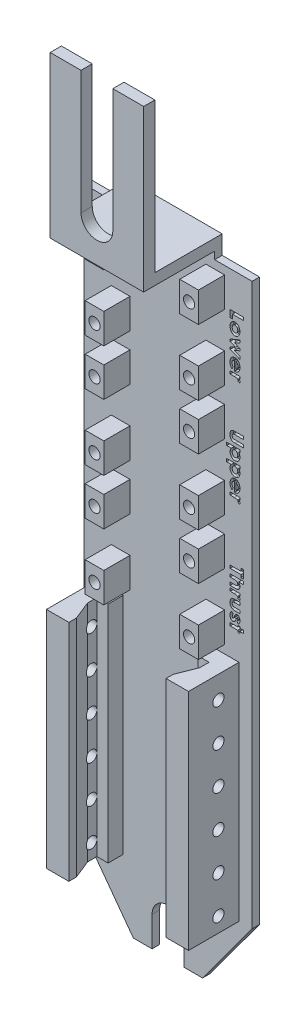
SolidWorks part; units mm, degrees
ref_plane "Front Plane" through (0, 0, 0) normal (0, 0, 1) x (1, 0, 0)
ref_plane "Top Plane" through (0, 0, 0) normal (0, 1, 0) x (1, 0, 0)
ref_plane "Right Plane" through (0, 0, 0) normal (1, 0, 0) x (0, 0, -1)
sketch "Sketch1" plane through (0, 0, 0) normal (0, 0, 1) x (1, 0, 0)
  line L1 (-12.65, -8.8) -> (12.65, -8.8) construction
  line L2 (-12.65, -8.8) -> (-12.65, 8.8) construction
  line L3 (-12.65, 8.8) -> (12.65, 8.8) construction
  line L4 (12.65, -8.8) -> (12.65, 8.8) construction
  line L5 (-12.65, -8.8) -> (12.65, 8.8) construction
  line L6 (-12.65, 8.8) -> (12.65, -8.8) construction
  line L7 (-15.15, 4.8) -> (-10.15, 4.8)
  line L8 (-15.15, 4.8) -> (-15.15, 12.8)
  line L9 (-15.15, 12.8) -> (-10.15, 12.8)
  line L10 (-10.15, 4.8) -> (-10.15, 12.8)
  line L11 (-15.15, 4.8) -> (-10.15, 12.8) construction
  line L12 (-15.15, 12.8) -> (-10.15, 4.8) construction
  line L13 (10.15, 4.8) -> (15.15, 4.8)
  line L14 (10.15, 4.8) -> (10.15, 12.8)
  line L15 (10.15, 12.8) -> (15.15, 12.8)
  line L16 (15.15, 4.8) -> (15.15, 12.8)
  line L17 (10.15, 4.8) -> (15.15, 12.8) construction
  line L18 (10.15, 12.8) -> (15.15, 4.8) construction
  line L19 (10.15, -4.8) -> (15.15, -4.8)
  line L20 (10.15, -4.8) -> (10.15, -12.8)
  line L21 (10.15, -12.8) -> (15.15, -12.8)
  line L22 (15.15, -4.8) -> (15.15, -12.8)
  line L23 (10.15, -4.8) -> (15.15, -12.8) construction
  line L24 (10.15, -12.8) -> (15.15, -4.8) construction
  line L25 (-15.15, -4.8) -> (-10.15, -4.8)
  line L26 (-15.15, -4.8) -> (-15.15, -12.8)
  line L27 (-15.15, -12.8) -> (-10.15, -12.8)
  line L28 (-10.15, -4.8) -> (-10.15, -12.8)
  line L29 (-15.15, -4.8) -> (-10.15, -12.8) construction
  line L30 (-15.15, -12.8) -> (-10.15, -4.8) construction
  circle A0 centre (-12.65, 8.8) radius 1.5
  circle A1 centre (12.65, 8.8) radius 1.5
  circle A2 centre (12.65, -8.8) radius 1.5
  circle A3 centre (-12.65, -8.8) radius 1.5
  point P0 (0, 0)
  dimension "D3" = 3
  dimension "D4" = 3
  dimension "D5" = 3
  dimension "D6" = 3
  dimension "D1" = 25.3
  dimension "D2" = 17.6
  dimension "D7" = 5
  dimension "D8" = 5
  dimension "D9" = 5
  dimension "D10" = 5
  dimension "D11" = 8
  dimension "D12" = 8
  dimension "D13" = 8
  dimension "D14" = 8
extrude "Boss-Extrude1" add sketch "Sketch1" along normal blind 7
sketch "Sketch2" plane through (0, 0, 0) normal (0, 0, -1) x (-1, 0, 0)
  line L1 (-22.5, -15) -> (22.5, -15)
  line L2 (-22.5, -15) -> (-22.5, 15)
  line L3 (-22.5, 15) -> (22.5, 15)
  line L4 (22.5, -15) -> (22.5, 15)
  line L5 (-22.5, -15) -> (22.5, 15) construction
  line L6 (-22.5, 15) -> (22.5, -15) construction
  point P0 (0, 0)
  dimension "D1" = 30
  dimension "D2" = 45
extrude "Boss-Extrude2" add sketch "Sketch2" along normal blind 2
pattern_linear "LPattern1" count 3 spacing 30 along (0, 1, 0) of "Boss-Extrude2", "Boss-Extrude1"
combine bodies "Combine1" operation type add bodies to combine 105 106 107
sketch "Sketch3" plane through (0, 0, 0) normal (0, 0, 1) x (1, 0, 0)
  line L0 (16.65, 72.4857) -> (16.65, -12.8559) construction
  line L1 (15.15, 47.2) -> (15.15, 55.2) construction
  text T0 "<b>    Lower       Upper         Thrust</b>" font "Century Gothic" height 3.5
  dimension "D1" = 1.5
extrude "Cut-Extrude1" cut sketch "Sketch3" against normal blind 1
sketch "Sketch6" plane through (0, 0, 0) normal (1, 0, 0) x (0, 0, -1)
  line L0 (2, 75) -> (2, 80)
  line L1 (2, 80) -> (-16, 80)
  line L2 (-16, 80) -> (-16, 120)
  line L3 (-16, 120) -> (-19, 120)
  line L4 (-19, 120) -> (-19, 77)
  line L5 (-19, 77) -> (0, 77)
  line L6 (0, 77) -> (0, 75)
  line L7 (0, 75) -> (2, 75)
  dimension "D1" = 3
  dimension "D2" = 3
  dimension "D3" = 18
  dimension "D4" = 40
  dimension "D5" = 2
extrude "Boss-Extrude3" add sketch "Sketch6" along normal mid plane 25
sketch "Sketch7" plane through (0, 0, 19) normal (0, 0, 1) x (1, 0, 0)
  line L0 (12.5, 120) -> (12.5, 77) construction
  line L1 (12.5, 77) -> (-12.5, 77) construction
  line L2 (-4.25, 87) -> (-4.25, 122.0762)
  line L3 (-4.25, 122.0762) -> (4.25, 122.0762)
  line L4 (4.25, 122.0762) -> (4.25, 87)
  line L5 (12.5, 120) -> (-12.5, 120) construction
  arc A0 (-4.25, 87) -> (4.25, 87) centre (0, 87) ccw
  dimension "D1" = 8.5
  dimension "D2" = 12.5
  dimension "D3" = 10
  dimension "D4" = 2.0762
extrude "Cut-Extrude2" cut sketch "Sketch7" against normal blind 25
sketch "Sketch8" plane through (0, -15, 0) normal (0, -1, 0) x (1, 0, 0)
  line L0 (-22.5, -2) -> (22.5, -2)
  line L1 (22.5, -2) -> (22.5, 0)
  line L2 (22.5, 0) -> (19, 0)
  line L3 (22.5, 0) -> (-22.5, 0) construction
  line L4 (19, 0) -> (19, 13.5)
  line L5 (19, 13.5) -> (13, 13.5)
  line L6 (13, 13.5) -> (13, 11.5)
  line L7 (13, 11.5) -> (15, 6.5)
  line L8 (15, 6.5) -> (15, 4)
  line L9 (15, 4) -> (12, 4)
  line L10 (12, 4) -> (12, 0)
  line L11 (10.15, 0) -> (15.15, 0) construction
  line L12 (12, 0) -> (-12, 0)
  line L13 (-15.15, 0) -> (-10.15, 0) construction
  line L14 (-12, 0) -> (-12, 4)
  line L15 (-12, 4) -> (-15, 4)
  line L16 (-15, 4) -> (-15, 6.5)
  line L17 (-15, 6.5) -> (-13, 11.5)
  line L18 (-13, 11.5) -> (-13, 13.5)
  line L19 (-13, 13.5) -> (-19, 13.5)
  line L20 (-19, 13.5) -> (-19, 0)
  line L21 (-19, 0) -> (-22.5, 0)
  line L22 (-22.5, 0) -> (-22.5, -2)
  point P4 (14.15, 9.2436)
  point P31 (-12.5, 9.5)
  point P34 (-14.65, 5.2806)
  point P35 (-14.5, 4.7852)
  dimension "D1" = 3
  dimension "D2" = 2
  dimension "D3" = 4
  dimension "D4" = 3
  dimension "D5" = 2
  dimension "D6" = 4
  dimension "D7" = 2.5
  dimension "D8" = 2.5
  dimension "D9" = 5
  dimension "D10" = 5
  dimension "D11" = 2
  dimension "D12" = 2
  dimension "D13" = 4
  dimension "D14" = 4
  dimension "D15" = 15
  dimension "D16" = 15
extrude "Boss-Extrude4" add sketch "Sketch8" along normal blind 60
sketch "Sketch9" plane through (0, 0, 0) normal (0, 0, 1) x (1, 0, 0)
  line L0 (0, 0) -> (0, -112.7652) construction
  line L1 (-4.25, -85) -> (-4.25, -93)
  line L2 (-4.25, -93) -> (-9.25, -93)
  line L3 (-9.25, -93) -> (-22.5, -75)
  line L4 (-22.5, -75) -> (22.5, -75)
  line L5 (22.5, -75) -> (9.25, -93)
  line L6 (9.25, -93) -> (4.25, -93)
  line L7 (4.25, -93) -> (4.25, -85)
  line L8 (-4.25, -93) -> (4.25, -93) construction
  arc A0 (4.25, -85) -> (-4.25, -85) centre (0, -85) ccw
  dimension "D1" = 4.25
  dimension "D2" = 5
  dimension "D3" = 5
  dimension "D4" = 8
  dimension "D5" = 10
extrude "Boss-Extrude5" add sketch "Sketch9" against normal blind 2
sketch "Sketch10" plane through (19, 0, 0) normal (1, 0, 0) x (0, 0, -1)
  line L0 (0, 75) -> (0, -75) construction
  line L1 (0, -75) -> (-13.5, -75) construction
  circle A0 centre (-5.5, -71) radius 1.5
  dimension "D1" = 3
  dimension "D2" = 5.5
  dimension "D3" = 4
extrude "Cut-Extrude3" cut sketch "Sketch10" against normal blind 52
pattern_linear "LPattern2" count 6 spacing 10 along (0, 1, 0) of "Cut-Extrude3"
equation "\"D4@Sketch1\"=\"D3@Sketch1\""
equation "\"D5@Sketch1\"=\"D3@Sketch1\""
equation "\"D6@Sketch1\"=\"D3@Sketch1\""
equation "\"D8@Sketch1\"=\"D7@Sketch1\""
equation "\"D9@Sketch1\"=\"D7@Sketch1\""
equation "\"D10@Sketch1\"=\"D7@Sketch1\""
equation "\"D12@Sketch1\"=\"D11@Sketch1\""
equation "\"D13@Sketch1\"=\"D11@Sketch1\""
equation "\"D14@Sketch1\"=\"D11@Sketch1\""
